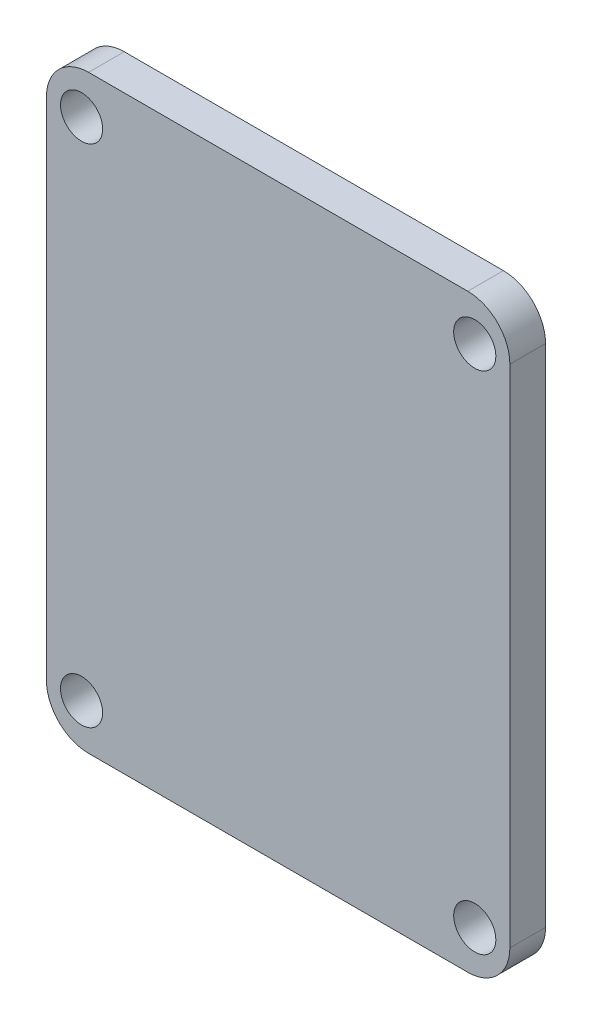
SolidWorks part; units mm, degrees
ref_plane "Front Plane" through (0, 0, 0) normal (1, 0, 0) x (0, 1, 0)
ref_plane "Top Plane" through (0, 0, 0) normal (0, 0, 1) x (0, 1, 0)
ref_plane "Right Plane" through (0, 0, 0) normal (0, 1, 0) x (-1, 0, 0)
sketch "Sketch1" plane through (0, 0, 0) normal (0, 0, 1) x (0, 1, 0)
  line L0 (-18, 14) -> (-18, -14) construction
  line L1 (-21, 16.5) -> (21, 16.5)
  line L2 (-21, 16.5) -> (-21, -16.5)
  line L3 (-21, -16.5) -> (21, -16.5)
  line L4 (21, 16.5) -> (21, -16.5)
  line L5 (-21, 16.5) -> (21, -16.5) construction
  line L6 (-21, -16.5) -> (21, 16.5) construction
  line L7 (-18, -14) -> (18, -14) construction
  line L8 (18, -14) -> (18, 14) construction
  line L9 (-18, 14) -> (18, 14) construction
  line L10 (0, 14) -> (0, 16.5) construction
  line L11 (-18, 0) -> (-21, 0) construction
  circle A0 centre (-18, 14) radius 1.5
  circle A1 centre (-18, -14) radius 1.5
  circle A2 centre (18, 14) radius 1.5
  circle A3 centre (18, -14) radius 1.5
  point P0 (0, 0)
  dimension "D5" = 3
  dimension "D1" = 42
  dimension "D2" = 33
  dimension "D3" = 36
  dimension "D4" = 28
extrude "Boss-Extrude1" add sketch "Sketch1" along normal blind 2.54
fillet "Fillet1" radius 3 4 edges at (16.5, 21, 1.27) (-16.5, 21, 1.27) (-16.5, -21, 1.27) (16.5, -21, 1.27)
